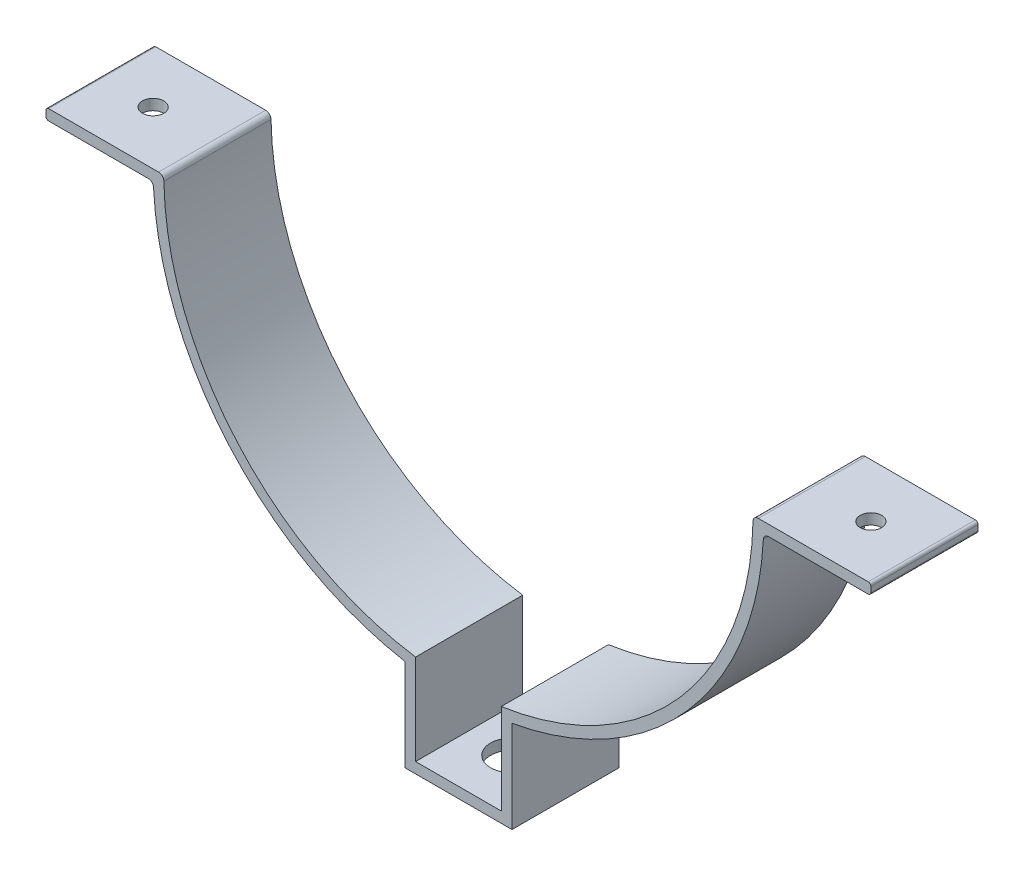
SolidWorks part; units mm, degrees
material "AISI 1020"
ref_plane "Alzado" through (0, 0, 0) normal (0, 0, 1) x (1, 0, 0)
ref_plane "Planta" through (0, 0, 0) normal (0, 1, 0) x (1, 0, 0)
ref_plane "Vista lateral" through (0, 0, 0) normal (1, 0, 0) x (0, 0, -1)
sketch "Croquis1" plane through (0, 0, 0) normal (0, 0, 1) x (1, 0, 0)
  line L2 (-57, 0) -> (-55.9911, 0)
  line L3 (-57, 0) -> (-76.5, 0)
  line L4 (-56.9649, 2) -> (56.9649, 2) construction
  line L5 (-77, -0.5) -> (-77, -1.5)
  line L6 (-76.5, -2) -> (-57.9224, -2)
  line L7 (0, -71.3129) -> (0, -73.3129) construction
  line L8 (-55, 0) -> (55, 0) construction
  line L9 (76.5, -2) -> (57.9224, -2)
  line L10 (77, -0.5) -> (77, -1.5)
  line L11 (57, 0) -> (76.5, 0)
  line L12 (57, 0) -> (55.9911, 0)
  line L13 (-10, -73.3129) -> (10, -73.3129)
  line L14 (-8, -56.4358) -> (-8, -71.3129)
  line L15 (-8, -71.3129) -> (8, -71.3129)
  line L16 (-10, -73.3129) -> (-10, -56.116)
  line L17 (10, -73.3129) -> (10, -56.116)
  line L18 (8, -56.4358) -> (8, -71.3129)
  line L19 (-8, -56.4358) -> (-8, -54.4151)
  line L20 (8, -56.4358) -> (8, -54.4151)
  arc A0 (-54.9912, -0.9821) -> (-8, -54.4151) centre (0, 0) ccw
  arc A1 (-56.9237, -2.9483) -> (-10, -56.116) centre (0, 0) ccw
  arc A2 (-56.9649, 2) -> (56.9649, 2) centre (0, 0) ccw construction
  arc A3 (-56.9237, -2.9483) -> (-57.9224, -2) centre (-57.9224, -3) ccw
  arc A4 (-55, 0) -> (55, 0) centre (0, 0) ccw construction
  arc A5 (-54.9912, -0.9821) -> (-55.9911, 0) centre (-55.9911, -1) ccw
  arc A6 (-77, -0.5) -> (-76.5, 0) centre (-76.5, -0.5) cw
  arc A7 (-77, -1.5) -> (-76.5, -2) centre (-76.5, -1.5) ccw
  arc A8 (77, -1.5) -> (76.5, -2) centre (76.5, -1.5) cw
  arc A9 (77, -0.5) -> (76.5, 0) centre (76.5, -0.5) ccw
  arc A10 (54.9912, -0.9821) -> (55.9911, 0) centre (55.9911, -1) cw
  arc A11 (56.9237, -2.9483) -> (57.9224, -2) centre (57.9224, -3) cw
  arc A13 (10, -56.116) -> (56.9237, -2.9483) centre (0, 0) ccw
  arc A14 (8, -54.4151) -> (54.9912, -0.9821) centre (0, 0) ccw
  point P19 (77, -2)
  point P21 (-77, 0)
  point P24 (-77, -2)
  point P37 (77, 0)
  point P47 (0, -71.3129)
  dimension "D1" = 2
  dimension "D4" = 55
  dimension "D5" = 1
  dimension "D6" = 1
  dimension "D7" = 0.5
  dimension "D8" = 0.5
  dimension "D2" = 2
  dimension "D3" = 20
  dimension "D10" = 2
  dimension "D11" = 2
  dimension "D12" = 10
extrude "Saliente-Extruir2" add sketch "Croquis1" along normal blind 20
sketch "Croquis3" plane through (0, -73.3129, 0) normal (0, -1, 0) x (1, 0, 0)
  circle A0 centre (0, 10) radius 4
  dimension "D1" = 8
  dimension "D2" = 10
extrude "Cortar-Extruir1" cut sketch "Croquis3" against normal through all both and the other way through all contours A0
sketch "Croquis4" plane through (0, 0, 0) normal (0, 1, 0) x (1, 0, 0)
  line L0 (76.5, -20) -> (55.9911, -20) construction
  line L1 (77, -20) -> (77, 0) construction
  circle A0 centre (67, -10) radius 2
  dimension "D1" = 4
  dimension "D2" = 10
  dimension "D3" = 10
extrude "Cortar-Extruir2" cut sketch "Croquis4" against normal through all both and the other way through all
mirror "Simetría1" about plane through (0, 0, 0) normal (1, 0, 0) of "Cortar-Extruir2"
